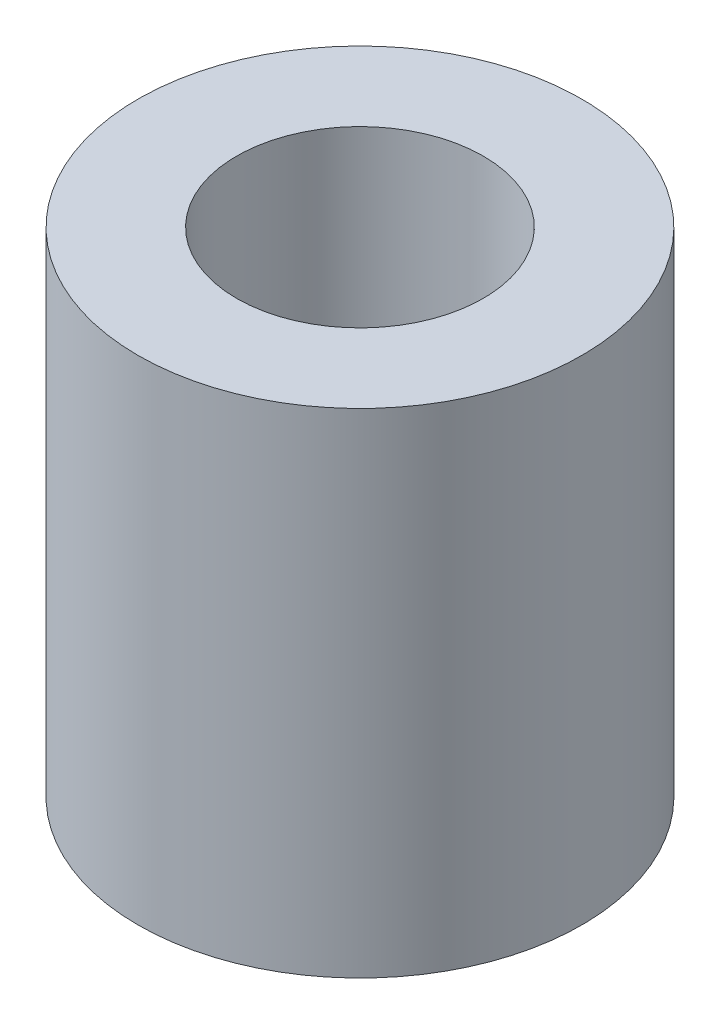
SolidWorks part; units mm, degrees
material "Brass"
ref_plane "Front Plane" through (0, 0, 0) normal (0, 0, 1) x (1, 0, 0)
ref_plane "Top Plane" through (0, 0, 0) normal (0, 1, 0) x (1, 0, 0)
ref_plane "Right Plane" through (0, 0, 0) normal (1, 0, 0) x (0, 0, -1)
sketch "Sketch1" plane through (0, 0, 0) normal (0, 1, 0) x (1, 0, 0)
  circle A0 centre (0, 0) radius 2.5
  circle A1 centre (0, 0) radius 4.5
  dimension "D1" = 5
  dimension "D2" = 9
extrude "Boss-Extrude1" add sketch "Sketch1" along normal mid plane 10
